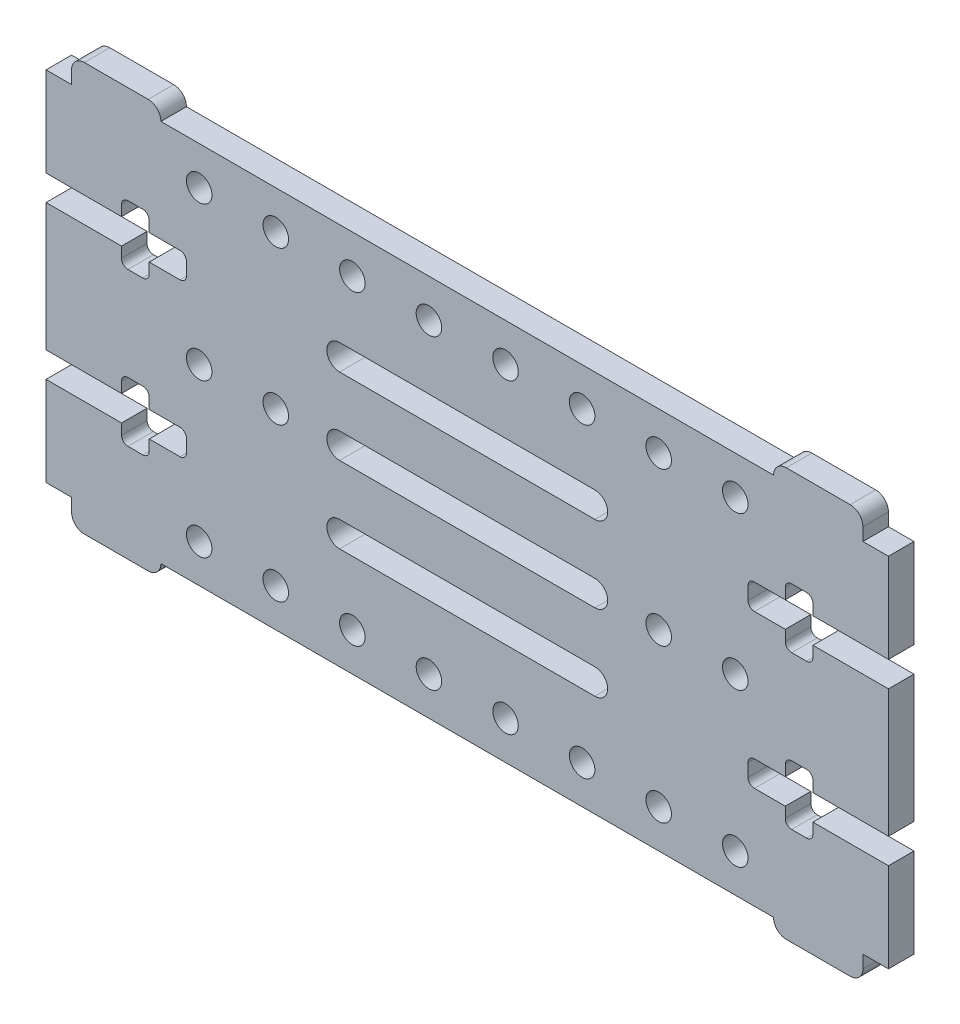
SolidWorks part; units mm, degrees
ref_plane "Alzado" through (0, 0, 0) normal (0, 0, 1) x (1, 0, 0)
ref_plane "Planta" through (0, 0, 0) normal (0, 1, 0) x (1, 0, 0)
ref_plane "Vista lateral" through (0, 0, 0) normal (1, 0, 0) x (0, 0, -1)
sketch "Model" plane through (0, 0, 0) normal (0, 0, 1) x (1, 0, 0)
  line L0 (-1383.7275, 378.9082) -> (-1386.7275, 378.9082)
  line L1 (-1383.7275, 336.9082) -> (-1386.7275, 336.9082)
  line L2 (-1388.2275, 381.9082) -> (-1395.7279, 381.9082)
  line L3 (-1482.7275, 365.4082) -> (-1482.7275, 350.4082)
  line L4 (-1395.7279, 333.9082) -> (-1388.2275, 333.9082)
  line L5 (-1479.7275, 378.9082) -> (-1482.7275, 378.9082)
  line L6 (-1479.7275, 336.9082) -> (-1482.7275, 336.9082)
  line L7 (-1479.7275, 378.9082) -> (-1479.7275, 380.4082)
  line L8 (-1479.7275, 336.9082) -> (-1479.7275, 335.4082)
  line L9 (-1386.7275, 336.9082) -> (-1386.7275, 335.4082)
  line L10 (-1386.7275, 378.9082) -> (-1386.7275, 380.4082)
  line L11 (-1383.7275, 378.9082) -> (-1383.7275, 368.4082)
  line L12 (-1383.7275, 347.4082) -> (-1383.7275, 336.9082)
  line L13 (-1482.7275, 347.4082) -> (-1482.7275, 336.9082)
  line L14 (-1482.7275, 378.9082) -> (-1482.7275, 368.4082)
  line L15 (-1448.2275, 350.4082) -> (-1418.2275, 350.4082)
  line L16 (-1448.2275, 347.4082) -> (-1418.2275, 347.4082)
  line L17 (-1448.2275, 359.4082) -> (-1418.2275, 359.4082)
  line L18 (-1448.2275, 356.4082) -> (-1418.2275, 356.4082)
  line L19 (-1448.2275, 368.4082) -> (-1418.2275, 368.4082)
  line L20 (-1448.2275, 365.4082) -> (-1418.2275, 365.4082)
  line L21 (-1383.7275, 350.4082) -> (-1383.7275, 365.4082)
  line L22 (-1383.7275, 347.4082) -> (-1392.6025, 347.4082)
  line L23 (-1392.6025, 350.4082) -> (-1383.7275, 350.4082)
  line L24 (-1399.4775, 350.4082) -> (-1395.8525, 350.4082)
  line L25 (-1395.8525, 347.4082) -> (-1399.4775, 347.4082)
  line L26 (-1400.2275, 348.1582) -> (-1400.2275, 349.6582)
  line L27 (-1473.8525, 347.4082) -> (-1482.7275, 347.4082)
  line L28 (-1482.7275, 350.4082) -> (-1473.8525, 350.4082)
  line L29 (-1466.9775, 347.4082) -> (-1470.6025, 347.4082)
  line L30 (-1470.6025, 350.4082) -> (-1466.9775, 350.4082)
  line L31 (-1466.2275, 349.6582) -> (-1466.2275, 348.1582)
  line L32 (-1473.1025, 352.4082) -> (-1471.3525, 352.4082)
  line L33 (-1471.3525, 345.4082) -> (-1473.1025, 345.4082)
  line L34 (-1473.8525, 350.4082) -> (-1473.8525, 351.6582)
  line L35 (-1470.6025, 350.4082) -> (-1470.6025, 351.6582)
  line L36 (-1473.8525, 347.4082) -> (-1473.8525, 346.1582)
  line L37 (-1470.6025, 347.4082) -> (-1470.6025, 346.1582)
  line L38 (-1395.1025, 352.4082) -> (-1393.3525, 352.4082)
  line L39 (-1393.3525, 345.4082) -> (-1395.1025, 345.4082)
  line L40 (-1395.8525, 350.4082) -> (-1395.8525, 351.6582)
  line L41 (-1392.6025, 350.4082) -> (-1392.6025, 351.6582)
  line L42 (-1395.8525, 347.4082) -> (-1395.8525, 346.1582)
  line L43 (-1392.6025, 347.4082) -> (-1392.6025, 346.1582)
  line L44 (-1473.8525, 365.4082) -> (-1482.7275, 365.4082)
  line L45 (-1482.7275, 368.4082) -> (-1473.8525, 368.4082)
  line L46 (-1466.9775, 365.4082) -> (-1470.6025, 365.4082)
  line L47 (-1470.6025, 368.4082) -> (-1466.9775, 368.4082)
  line L48 (-1466.2275, 367.6582) -> (-1466.2275, 366.1582)
  line L49 (-1473.1025, 370.4082) -> (-1471.3525, 370.4082)
  line L50 (-1471.3525, 363.4082) -> (-1473.1025, 363.4082)
  line L51 (-1473.8525, 368.4082) -> (-1473.8525, 369.6582)
  line L52 (-1470.6025, 368.4082) -> (-1470.6025, 369.6582)
  line L53 (-1473.8525, 365.4082) -> (-1473.8525, 364.1582)
  line L54 (-1470.6025, 365.4082) -> (-1470.6025, 364.1582)
  line L55 (-1383.7275, 365.4082) -> (-1392.6025, 365.4082)
  line L56 (-1392.6025, 368.4082) -> (-1383.7275, 368.4082)
  line L57 (-1399.4775, 368.4082) -> (-1395.8525, 368.4082)
  line L58 (-1395.8525, 365.4082) -> (-1399.4775, 365.4082)
  line L59 (-1400.2275, 366.1582) -> (-1400.2275, 367.6582)
  line L60 (-1395.1025, 370.4082) -> (-1393.3525, 370.4082)
  line L61 (-1393.3525, 363.4082) -> (-1395.1025, 363.4082)
  line L62 (-1395.8525, 368.4082) -> (-1395.8525, 369.6582)
  line L63 (-1392.6025, 368.4082) -> (-1392.6025, 369.6582)
  line L64 (-1395.8525, 365.4082) -> (-1395.8525, 364.1582)
  line L65 (-1392.6025, 365.4082) -> (-1392.6025, 364.1582)
  line L66 (-1469.2279, 335.4082) -> (-1397.2279, 335.4082)
  line L67 (-1397.2279, 380.4082) -> (-1469.2279, 380.4082)
  line L68 (-1478.2275, 333.9082) -> (-1470.7279, 333.9082)
  line L69 (-1470.7279, 381.9082) -> (-1478.2275, 381.9082)
  circle A0 centre (-1401.7282, 357.9082) radius 1.5
  circle A1 centre (-1464.7282, 357.9082) radius 1.5
  arc A2 (-1448.2275, 350.4082) -> (-1448.2275, 347.4082) centre (-1448.2275, 348.9082) ccw
  arc A3 (-1418.2275, 347.4082) -> (-1418.2275, 350.4082) centre (-1418.2275, 348.9082) ccw
  arc A4 (-1418.2275, 365.4082) -> (-1418.2275, 368.4082) centre (-1418.2275, 366.9082) ccw
  circle A5 centre (-1455.7282, 357.9082) radius 1.5
  circle A6 centre (-1410.7282, 357.9082) radius 1.5
  arc A7 (-1448.2275, 359.4082) -> (-1448.2275, 356.4082) centre (-1448.2275, 357.9082) ccw
  arc A8 (-1418.2275, 356.4082) -> (-1418.2275, 359.4082) centre (-1418.2275, 357.9082) ccw
  circle A9 centre (-1464.7282, 375.9082) radius 1.5
  circle A10 centre (-1455.7282, 375.9082) radius 1.5
  circle A11 centre (-1446.7282, 375.9082) radius 1.5
  circle A12 centre (-1437.7282, 375.9082) radius 1.5
  circle A13 centre (-1428.7282, 375.9082) radius 1.5
  circle A14 centre (-1419.7282, 375.9082) radius 1.5
  circle A15 centre (-1410.7282, 375.9082) radius 1.5
  circle A16 centre (-1401.7282, 375.9082) radius 1.5
  circle A17 centre (-1464.7282, 339.9082) radius 1.5
  circle A18 centre (-1455.7282, 339.9082) radius 1.5
  circle A19 centre (-1446.7282, 339.9082) radius 1.5
  circle A20 centre (-1437.7282, 339.9082) radius 1.5
  circle A21 centre (-1428.7282, 339.9082) radius 1.5
  circle A22 centre (-1419.7282, 339.9082) radius 1.5
  circle A23 centre (-1410.7282, 339.9082) radius 1.5
  circle A24 centre (-1401.7282, 339.9082) radius 1.5
  arc A25 (-1448.2275, 368.4082) -> (-1448.2275, 365.4082) centre (-1448.2275, 366.9082) ccw
  arc A26 (-1473.1025, 352.4082) -> (-1473.8525, 351.6582) centre (-1473.1025, 351.6582) ccw
  arc A27 (-1470.6025, 351.6582) -> (-1471.3525, 352.4082) centre (-1471.3525, 351.6582) ccw
  arc A28 (-1471.3525, 345.4082) -> (-1470.6025, 346.1582) centre (-1471.3525, 346.1582) ccw
  arc A29 (-1473.8525, 346.1582) -> (-1473.1025, 345.4082) centre (-1473.1025, 346.1582) ccw
  arc A30 (-1466.2275, 349.6582) -> (-1466.9775, 350.4082) centre (-1466.9775, 349.6582) ccw
  arc A31 (-1466.9775, 347.4082) -> (-1466.2275, 348.1582) centre (-1466.9775, 348.1582) ccw
  arc A32 (-1399.4775, 350.4082) -> (-1400.2275, 349.6582) centre (-1399.4775, 349.6582) ccw
  arc A33 (-1400.2275, 348.1582) -> (-1399.4775, 347.4082) centre (-1399.4775, 348.1582) ccw
  arc A34 (-1395.1025, 352.4082) -> (-1395.8525, 351.6582) centre (-1395.1025, 351.6582) ccw
  arc A35 (-1392.6025, 351.6582) -> (-1393.3525, 352.4082) centre (-1393.3525, 351.6582) ccw
  arc A36 (-1393.3525, 345.4082) -> (-1392.6025, 346.1582) centre (-1393.3525, 346.1582) ccw
  arc A37 (-1395.8525, 346.1582) -> (-1395.1025, 345.4082) centre (-1395.1025, 346.1582) ccw
  arc A38 (-1473.1025, 370.4082) -> (-1473.8525, 369.6582) centre (-1473.1025, 369.6582) ccw
  arc A39 (-1470.6025, 369.6582) -> (-1471.3525, 370.4082) centre (-1471.3525, 369.6582) ccw
  arc A40 (-1471.3525, 363.4082) -> (-1470.6025, 364.1582) centre (-1471.3525, 364.1582) ccw
  arc A41 (-1473.8525, 364.1582) -> (-1473.1025, 363.4082) centre (-1473.1025, 364.1582) ccw
  arc A42 (-1466.2275, 367.6582) -> (-1466.9775, 368.4082) centre (-1466.9775, 367.6582) ccw
  arc A43 (-1466.9775, 365.4082) -> (-1466.2275, 366.1582) centre (-1466.9775, 366.1582) ccw
  arc A44 (-1399.4775, 368.4082) -> (-1400.2275, 367.6582) centre (-1399.4775, 367.6582) ccw
  arc A45 (-1400.2275, 366.1582) -> (-1399.4775, 365.4082) centre (-1399.4775, 366.1582) ccw
  arc A46 (-1395.1025, 370.4082) -> (-1395.8525, 369.6582) centre (-1395.1025, 369.6582) ccw
  arc A47 (-1392.6025, 369.6582) -> (-1393.3525, 370.4082) centre (-1393.3525, 369.6582) ccw
  arc A48 (-1393.3525, 363.4082) -> (-1392.6025, 364.1582) centre (-1393.3525, 364.1582) ccw
  arc A49 (-1395.8525, 364.1582) -> (-1395.1025, 363.4082) centre (-1395.1025, 364.1582) ccw
  arc A50 (-1478.2275, 381.9082) -> (-1479.7275, 380.4082) centre (-1478.2275, 380.4082) ccw
  arc A52 (-1469.2279, 380.4082) -> (-1470.7279, 381.9082) centre (-1470.7279, 380.4082) ccw
  arc A53 (-1395.7279, 381.9082) -> (-1397.2279, 380.4082) centre (-1395.7279, 380.4082) ccw
  arc A54 (-1386.7275, 380.4082) -> (-1388.2275, 381.9082) centre (-1388.2275, 380.4082) ccw
  arc A55 (-1388.2275, 333.9082) -> (-1386.7275, 335.4082) centre (-1388.2275, 335.4082) ccw
  arc A56 (-1397.2279, 335.4082) -> (-1395.7279, 333.9082) centre (-1395.7279, 335.4082) ccw
  arc A57 (-1479.7275, 335.4082) -> (-1478.2275, 333.9082) centre (-1478.2275, 335.4082) ccw
  arc A58 (-1470.7279, 333.9082) -> (-1469.2279, 335.4082) centre (-1470.7279, 335.4082) ccw
extrude "Saliente-Extruir1" add sketch "Model" along normal blind 3
